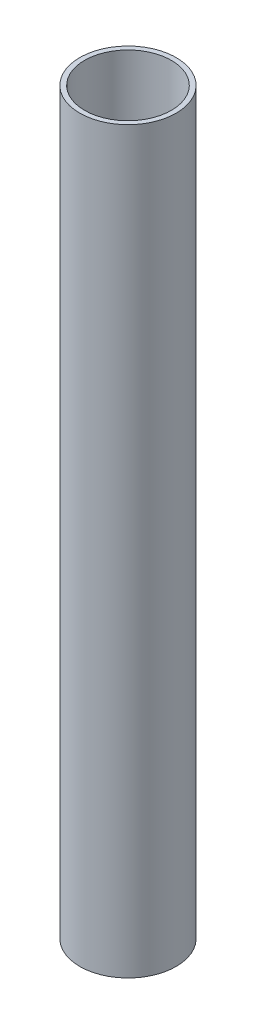
SolidWorks part; units mm, degrees
ref_plane "Спереди" through (0, 0, 0) normal (0, 0, 1) x (1, 0, 0)
ref_plane "Сверху" through (0, 0, 0) normal (0, 1, 0) x (1, 0, 0)
ref_plane "Справа" through (0, 0, 0) normal (1, 0, 0) x (0, 0, -1)
other "Configuration Table"
sketch "Sketch1" plane through (0, 0, 0) normal (0, 1, 0) x (1, 0, 0)
  circle A0 centre (0, 0) radius 15
  circle A1 centre (0, 0) radius 13.5
  dimension "D1" = 30
  dimension "D2" = 1.5
extrude "Boss-Extrude1" add sketch "Sketch1" along normal mid plane 230
